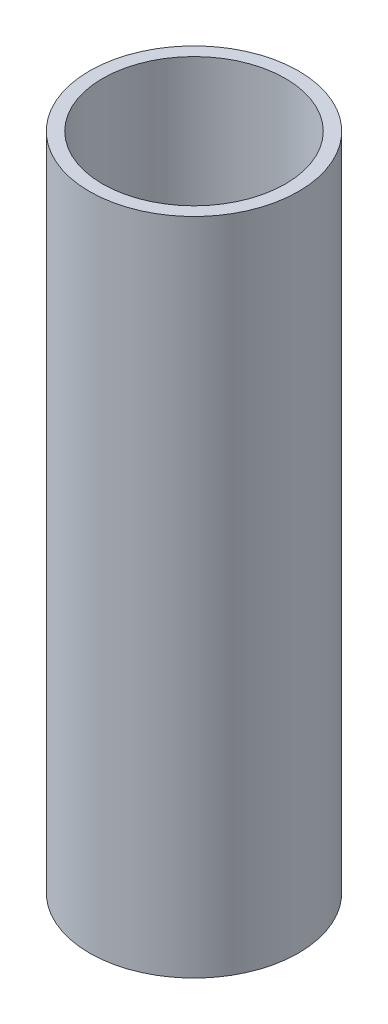
SolidWorks part; units mm, degrees
ref_plane "Front Plane" through (0, 0, 0) normal (0, 0, 1) x (1, 0, 0)
ref_plane "Top Plane" through (0, 0, 0) normal (0, 1, 0) x (1, 0, 0)
ref_plane "Right Plane" through (0, 0, 0) normal (1, 0, 0) x (0, 0, -1)
sketch "Sketch1" plane through (0, 0, 0) normal (0, 1, 0) x (1, 0, 0)
  circle A0 centre (0, 0) radius 7
  circle A1 centre (0, 0) radius 8
  dimension "D1" = 16
  dimension "D2" = 14
extrude "Boss-Extrude1" add sketch "Sketch1" along normal blind 50.5
equation "\"D1@Boss-Extrude1\"=sqr(5000*2) - 2 * 24.75"
